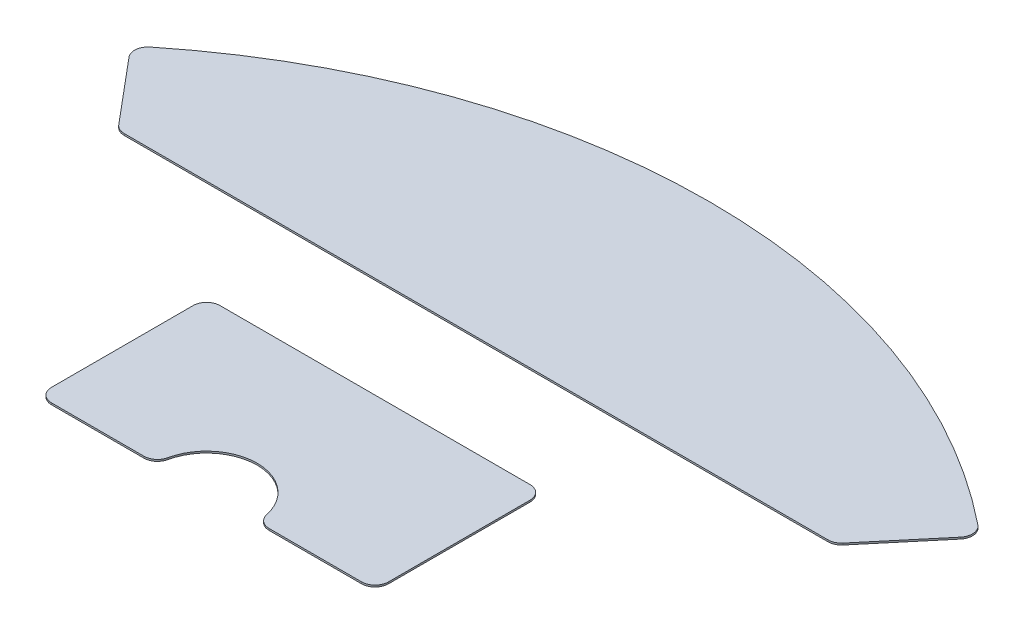
SolidWorks part; units mm, degrees
ref_plane "Front Plane" through (0, 0, 0) normal (0, 0, 1) x (1, 0, 0)
ref_plane "Top Plane" through (0, 0, 0) normal (0, 1, 0) x (1, 0, 0)
ref_plane "Right Plane" through (0, 0, 0) normal (1, 0, 0) x (0, 0, -1)
sketch "Sketch1" plane through (0, 0, 0) normal (0, 1, 0) x (1, 0, 0)
  line L0 (-7.5, 0) -> (-25, 0)
  line L1 (-25, 0) -> (-25, 25)
  line L2 (-25, 25) -> (25, 25)
  line L3 (25, 25) -> (25, 0)
  line L4 (25, 0) -> (7.5, 0)
  line L5 (0, 7.5) -> (0, 25) construction
  line L6 (0, 0) -> (0, 74.6641) construction
  line L7 (53.1451, 40) -> (-53.1451, 40)
  line L8 (-53.1451, 40) -> (-62.9932, 51.7365)
  line L10 (62.9932, 51.7365) -> (53.1451, 40)
  line L11 (0, 0) -> (-62.6507, 74.6641) construction
  line L12 (0, 0) -> (62.6507, 74.6641) construction
  line L13 (62.6507, 74.6641) -> (-62.6507, 74.6641) construction
  line L14 (0, -23.3359) -> (74.1413, 65.0223) construction
  line L15 (0, -23.3359) -> (-74.1413, 65.0223) construction
  circle A0 centre (0, 0) radius 7.5 construction
  arc A1 (7.5, 0) -> (-7.5, 0) centre (0, 0) ccw
  arc A2 (-62.9932, 51.7365) -> (62.9932, 51.7365) centre (0, -23.3359) cw
  point P19 (0, 74.6641)
  point P23 (0, 74.6641)
  dimension "D1" = 15
  dimension "D4" = 98
  dimension "D2" = 50
  dimension "D3" = 25
  dimension "D5" = 40
  dimension "D6" = 40
  dimension "D7" = 15
extrude "Boss-Extrude1" add sketch "Sketch1" along normal blind 0.254
fillet "Fillet1" radius 2 4 edges at (-53.1451, 0.127, -40) (-62.9932, 0.127, -51.7365) (62.9932, 0.127, -51.7365) (53.1451, 0.127, -40)
fillet "Fillet2" radius 2 6 edges at (-7.5, 0.127, 0) (-25, 0.127, 0) (-25, 0.127, -25) (25, 0.127, -25) (7.5, 0.127, 0) (25, 0.127, 0)
